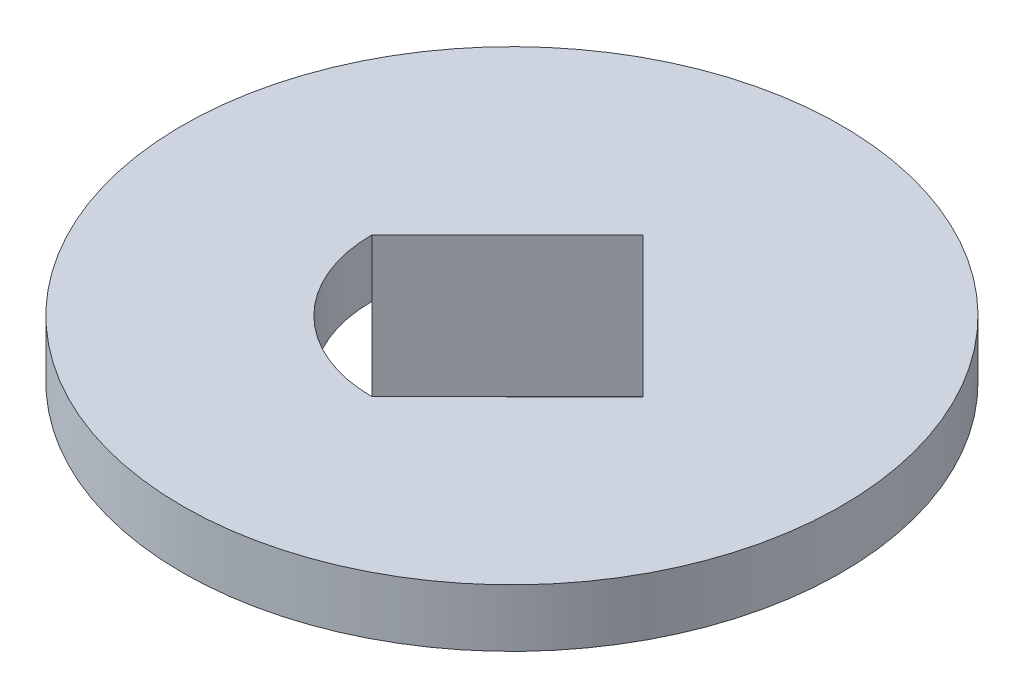
SolidWorks part; units mm, degrees
ref_plane "Front Plane" through (0, 0, 0) normal (0, 0, 1) x (1, 0, 0)
ref_plane "Top Plane" through (0, 0, 0) normal (0, 1, 0) x (1, 0, 0)
ref_plane "Right Plane" through (0, 0, 0) normal (1, 0, 0) x (0, 0, -1)
sketch "Sketch2" plane through (0, 0, 0) normal (0, 1, 0) x (1, 0, 0)
  line L4 (0.0293, -4.0302) -> (-3.9109, -0.09)
  line L5 (-3.9109, -0.09) -> (0.0883, 3.9091)
  line L6 (0.0883, 3.9091) -> (4.0302, -0.0293)
  circle A3 centre (0, 0) radius 10
  arc A7 (0.0293, -4.0302) -> (4.0302, -0.0293) centre (0, 0) cw
extrude "Boss-Extrude1" add sketch "Sketch2" along normal blind 1.75 contours A3
sketch "Sketch3" plane through (0, 0, 0) normal (0, -1, 0) x (1, 0, 0)
  line L7 (-4.25, 0) -> (-0.1383, -4.1117)
  line L8 (-0.1383, -4.1117) -> (4.1193, 0.1458)
  line L9 (4.1193, 0.1458) -> (0, 4.25)
  arc A0 (0, -4.25) -> (-4.25, 0) centre (0, 0) cw
  arc A1 (0, -4.25) -> (0, 4.25) centre (0, 0) ccw
extrude "Boss-Extrude2" add sketch "Sketch3" along normal blind 2.5
sketch "Sketch4" plane through (0, 0, 0) normal (0, -1, 0) x (1, 0, 0)
  line L4 (-0.1383, -4.1117) -> (4.1193, 0.1458)
  line L5 (4.1193, 0.1458) -> (0, 4.25)
  line L7 (-4.25, 0) -> (-0.1383, -4.1117)
  arc A0 (-4.25, 0) -> (0, 4.25) centre (0, 0) cw
extrude "Cut-Extrude1" cut sketch "Sketch4" against normal blind 2.5
